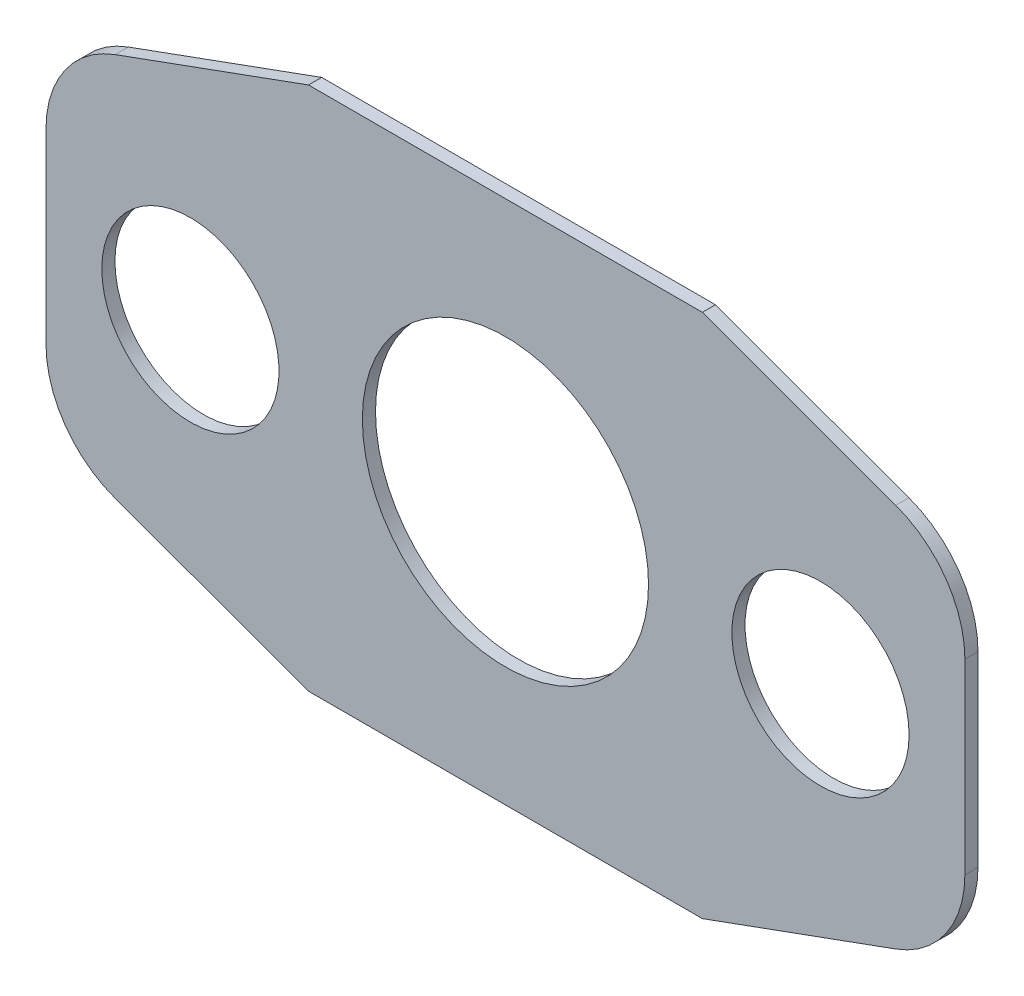
SolidWorks part; units mm, degrees
material "GASKET PAPER"
ref_plane "Front Plane" through (0, 0, 0) normal (0, 0, 1) x (1, 0, 0)
ref_plane "Top Plane" through (0, 0, 0) normal (0, 1, 0) x (1, 0, 0)
ref_plane "Right Plane" through (0, 0, 0) normal (1, 0, 0) x (0, 0, -1)
sketch "Sketch1" plane through (0, 0, 0) normal (0, 0, 1) x (1, 0, 0)
  line L0 (36.1231, 0) -> (0, 0) construction
  line L1 (0, 0) -> (0, 20.0312) construction
  line L2 (-15, 20) -> (15, 20)
  line L3 (15, 20) -> (29.7362, 14.6365)
  line L4 (35, 7.1189) -> (35, -7.1189)
  line L5 (15, -20) -> (29.7362, -14.6365)
  line L6 (-15, -20) -> (15, -20)
  line L7 (-15, 20) -> (-29.7362, 14.6365)
  line L8 (-35, 7.1189) -> (-35, -7.1189)
  line L9 (-15, -20) -> (-29.7362, -14.6365)
  arc A0 (29.7362, 14.6365) -> (35, 7.1189) centre (27, 7.1189) cw
  circle A1 centre (0, 0) radius 10.9
  circle A2 centre (24, 0) radius 6.75
  arc A3 (29.7362, -14.6365) -> (35, -7.1189) centre (27, -7.1189) ccw
  circle A4 centre (-24, 0) radius 6.75
  arc A5 (-29.7362, 14.6365) -> (-35, 7.1189) centre (-27, 7.1189) ccw
  arc A6 (-29.7362, -14.6365) -> (-35, -7.1189) centre (-27, -7.1189) cw
  point P13 (35, 0)
  point P20 (0, 20)
  point P27 (0, -20)
  dimension "D1" = 8
  dimension "D2" = 20
  dimension "D6" = 21.8
  dimension "D8" = 24
  dimension "D7" = 13.5
  dimension "D3" = 15
  dimension "D4" = 20
  dimension "D5" = 35
extrude "Boss-Extrude1" add sketch "Sketch1" against normal blind 1
